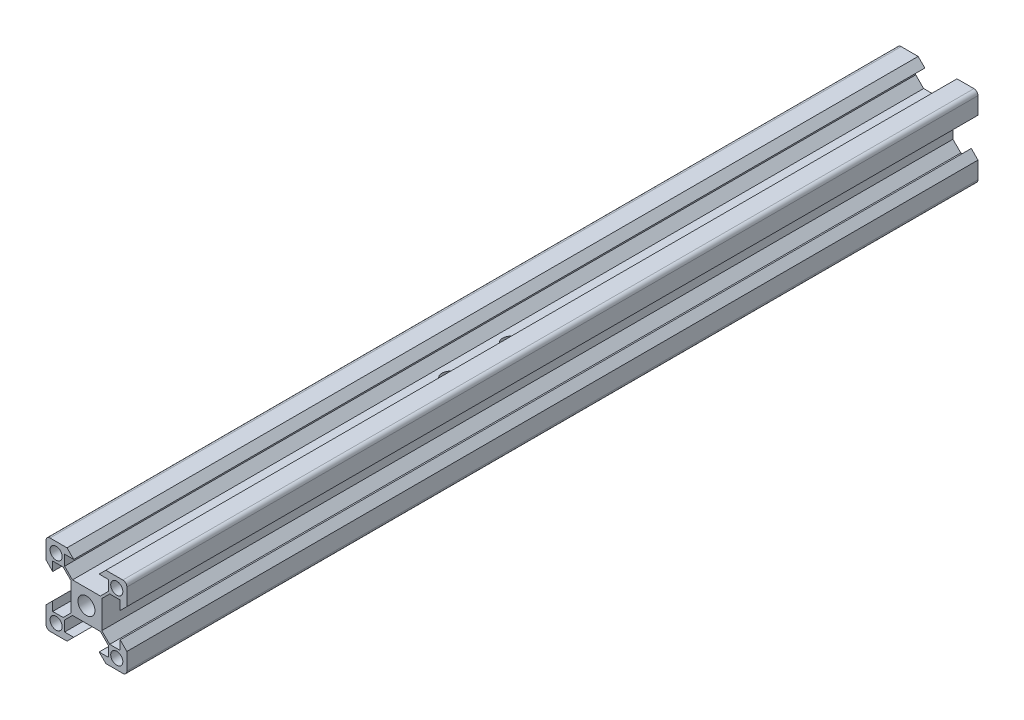
SolidWorks part; units mm, degrees
material "铝管"
ref_plane "前视基准面" through (0, 0, 0) normal (0, 0, 1) x (1, 0, 0)
ref_plane "上视基准面" through (0, 0, 0) normal (0, 1, 0) x (1, 0, 0)
ref_plane "右视基准面" through (0, 0, 0) normal (1, 0, 0) x (0, 0, -1)
sketch "草图1" plane through (0, 0, 0) normal (0, 0, 1) x (1, 0, 0)
  line L0 (0, 0) -> (-40.5659, 40.5659) construction
  line L1 (0, 0) -> (0, 75.5033) construction
  line L2 (-10, 10) -> (-10, 4.8)
  line L3 (-10, 4.8) -> (-8.34, 3.14)
  line L4 (-8.34, 3.14) -> (-8.34, 5.4)
  line L5 (-5.7536, 5.4) -> (-3.8, 3.4464)
  line L6 (-3.8, 3.4464) -> (-3.8, -3.4464)
  line L7 (-3.8, 0) -> (15.6715, 0) construction
  line L8 (-5.4, 8.34) -> (-5.4, 5.7536)
  line L9 (-3.4464, 3.8) -> (3.4464, 3.8)
  line L10 (-5.4, 5.7536) -> (-3.4464, 3.8)
  line L11 (-3.14, 8.34) -> (-5.4, 8.34)
  line L12 (-8.34, 5.4) -> (-5.7536, 5.4)
  line L13 (-4.8, 10) -> (-3.14, 8.34)
  line L14 (-10, 10) -> (-4.8, 10)
  line L15 (-10, -10) -> (-4.8, -10)
  line L16 (-4.8, -10) -> (-3.14, -8.34)
  line L17 (-8.34, -5.4) -> (-5.7536, -5.4)
  line L18 (-3.14, -8.34) -> (-5.4, -8.34)
  line L19 (-5.4, -5.7536) -> (-3.4464, -3.8)
  line L20 (-3.4464, -3.8) -> (3.4464, -3.8)
  line L21 (-5.4, -8.34) -> (-5.4, -5.7536)
  line L22 (-5.7536, -5.4) -> (-3.8, -3.4464)
  line L23 (-8.34, -3.14) -> (-8.34, -5.4)
  line L24 (-10, -4.8) -> (-8.34, -3.14)
  line L25 (-10, -10) -> (-10, -4.8)
  line L26 (10, -10) -> (10, -4.8)
  line L27 (10, -4.8) -> (8.34, -3.14)
  line L28 (8.34, -3.14) -> (8.34, -5.4)
  line L29 (5.7536, -5.4) -> (3.8, -3.4464)
  line L30 (5.4, -8.34) -> (5.4, -5.7536)
  line L31 (5.4, -5.7536) -> (3.4464, -3.8)
  line L32 (3.14, -8.34) -> (5.4, -8.34)
  line L33 (8.34, -5.4) -> (5.7536, -5.4)
  line L34 (4.8, -10) -> (3.14, -8.34)
  line L35 (10, -10) -> (4.8, -10)
  line L36 (10, 10) -> (4.8, 10)
  line L37 (4.8, 10) -> (3.14, 8.34)
  line L38 (8.34, 5.4) -> (5.7536, 5.4)
  line L39 (3.14, 8.34) -> (5.4, 8.34)
  line L40 (5.4, 5.7536) -> (3.4464, 3.8)
  line L41 (5.4, 8.34) -> (5.4, 5.7536)
  line L42 (3.8, 3.4464) -> (3.8, -3.4464)
  line L43 (5.7536, 5.4) -> (3.8, 3.4464)
  line L44 (8.34, 3.14) -> (8.34, 5.4)
  line L45 (10, 4.8) -> (8.34, 3.14)
  line L46 (10, 10) -> (10, 4.8)
  circle A0 centre (-7.5, 7.5) radius 1.5
  circle A1 centre (0, 0) radius 2.1
  circle A2 centre (-7.5, -7.5) radius 1.5
  circle A3 centre (7.5, -7.5) radius 1.5
  circle A4 centre (7.5, 7.5) radius 1.5
  point P54 (0, -3.8)
  point P64 (0, 3.8)
  dimension "D6" = 3
  dimension "D7" = 7.5
  dimension "D9" = 4.2
  dimension "D1" = 45
  dimension "D2" = 4.8
  dimension "D3" = 3.8
  dimension "D4" = 10
  dimension "D5" = 5.4
  dimension "D8" = 3.14
  dimension "D10" = 10
  dimension "D11" = 0.5
extrude "凸台-拉伸1" add sketch "草图1" along normal mid plane 210.5
fillet "圆角1" radius 1 4 edges at (-10, -10, 0) (10, -10, 0) (-10, 10, 0) (10, 10, 0)
sketch "草图2" plane through (0, 3.8, 0) normal (0, 1, 0) x (1, 0, 0)
  line L0 (0, -105.25) -> (0, 105.25) construction
  line L1 (3.4464, -105.25) -> (-3.4464, -105.25) construction
  line L2 (3.4464, 105.25) -> (-3.4464, 105.25) construction
  circle A0 centre (0, -15.25) radius 2.05
  circle A1 centre (0, -0.25) radius 2.05
  dimension "D1" = 15
  dimension "D2" = 4.1
  dimension "D3" = 105
extrude "切除-拉伸1" cut sketch "草图2" against normal through all both and the other way through all
